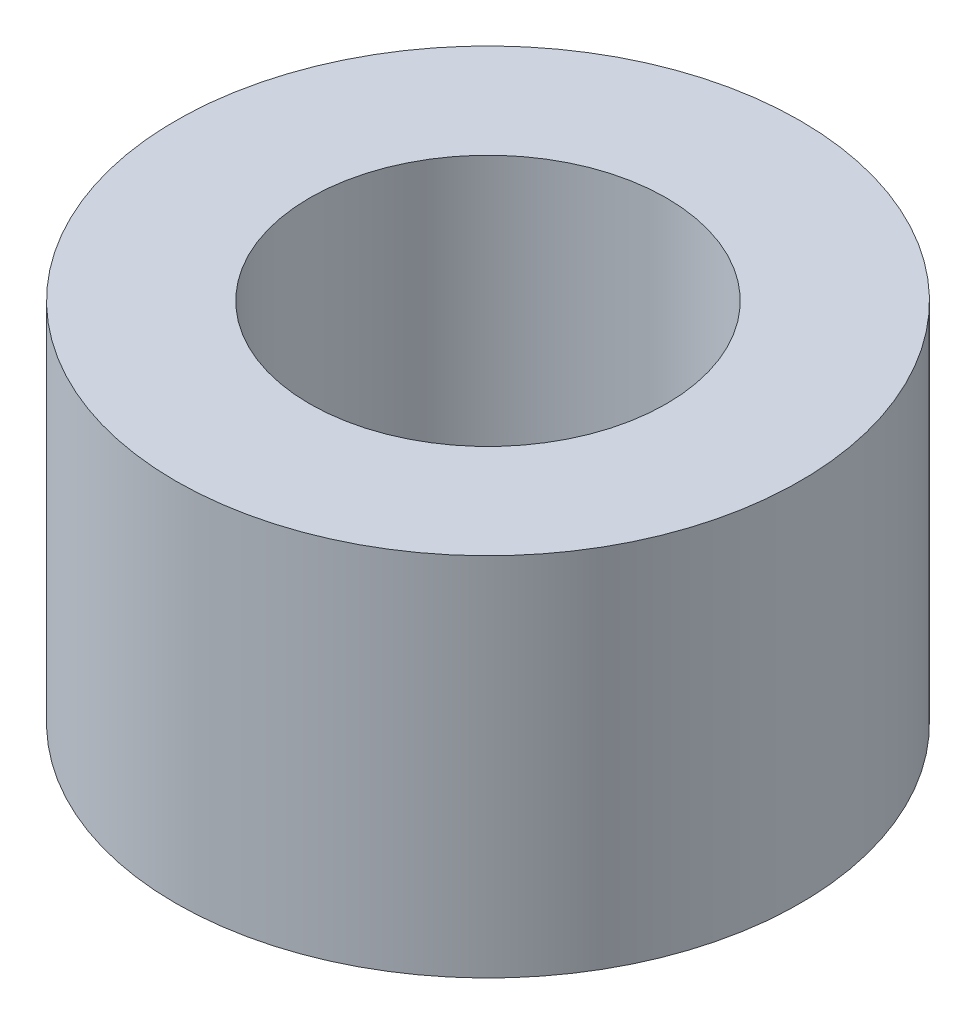
SolidWorks part; units mm, degrees
material "PLA"
ref_plane "Front Plane" through (0, 0, 0) normal (0, 0, 1) x (1, 0, 0)
ref_plane "Top Plane" through (0, 0, 0) normal (0, 1, 0) x (1, 0, 0)
ref_plane "Right Plane" through (0, 0, 0) normal (1, 0, 0) x (0, 0, -1)
ref_plane "Plane1" through (0, 0, 0) normal (0, 1, 0) x (1, 0, 0)
sketch "Sketch1" plane through (0, 0, 0) normal (0, 1, 0) x (1, 0, 0)
  circle A0 centre (0, 0) radius 3.5
  circle A1 centre (0, 0) radius 2
  dimension "D1" = 4
  dimension "D2" = 7
extrude "Boss-Extrude1" add sketch "Sketch1" along normal blind 4.1
